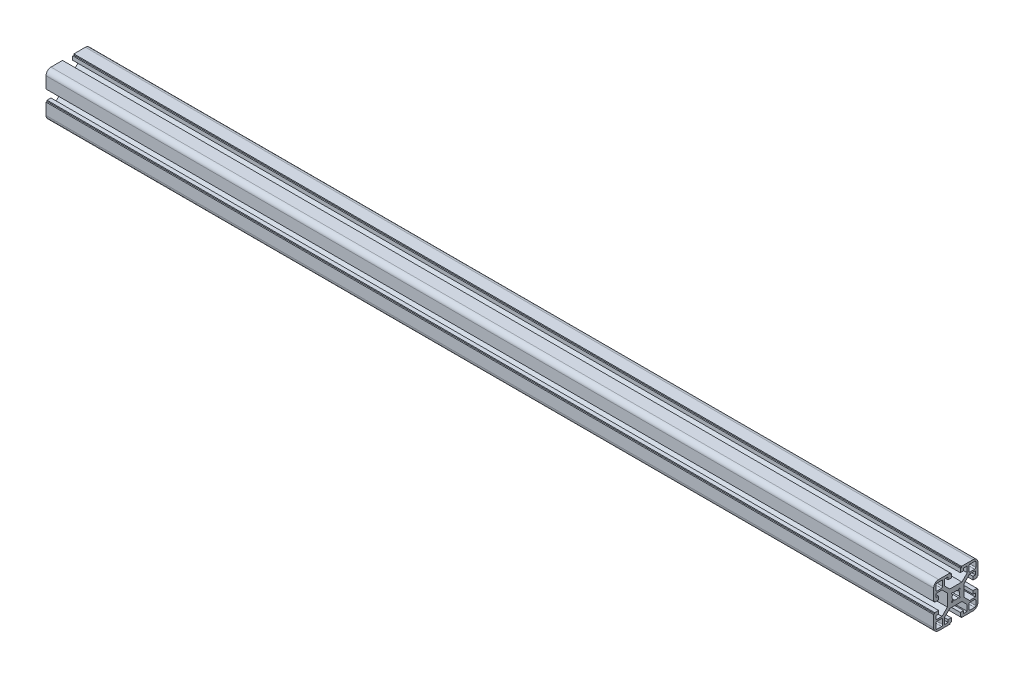
SolidWorks part; units mm, degrees
ref_plane "前视基准面" through (0, 0, 0) normal (0, 0, 1) x (1, 0, 0)
ref_plane "上视基准面" through (0, 0, 0) normal (0, 1, 0) x (1, 0, 0)
ref_plane "右视基准面" through (0, 0, 0) normal (1, 0, 0) x (0, 0, -1)
other "Configuration Table"
sketch "草图1" plane through (0, 0, 0) normal (1, 0, 0) x (0, 0, -1)
  line L0 (4.82, 19.28) -> (3.82, 19.28)
  line L1 (3.82, 19.28) -> (3.82, 15.78)
  line L2 (3.82, 15.78) -> (6.7364, 15.78)
  line L3 (6.7364, 15.78) -> (6.7364, 18.03)
  line L4 (6.7364, 18.03) -> (10.02, 18.03)
  line L5 (10.02, 18.03) -> (10.02, 12.7013)
  line L6 (10.02, 12.7013) -> (5.1987, 7.88)
  line L7 (5.1987, 7.88) -> (-5.7586, 7.88)
  line L8 (-5.7586, 7.88) -> (-10.58, 12.7013)
  line L9 (-10.58, 12.7013) -> (-10.58, 18.03)
  line L10 (-10.58, 18.03) -> (-7.2963, 18.03)
  line L11 (-7.2963, 18.03) -> (-7.2963, 15.78)
  line L12 (-7.2963, 15.78) -> (-4.38, 15.78)
  line L13 (-4.38, 15.78) -> (-4.38, 19.28)
  line L14 (-4.38, 19.28) -> (-5.38, 19.28)
  line L15 (-5.38, 19.28) -> (-5.38, 20.28)
  line L16 (-5.38, 20.28) -> (-15.78, 20.28)
  line L17 (-20.28, 15.78) -> (-20.28, 5.38)
  line L18 (-20.28, 5.38) -> (-19.28, 5.38)
  line L19 (-19.28, 5.38) -> (-19.28, 4.38)
  line L20 (-19.28, 4.38) -> (-15.78, 4.38)
  line L21 (-15.78, 4.38) -> (-15.78, 7.2963)
  line L22 (-15.78, 7.2963) -> (-18.03, 7.2963)
  line L23 (-18.03, 7.2963) -> (-18.03, 10.58)
  line L24 (-18.03, 10.58) -> (-12.7013, 10.58)
  line L25 (-12.7013, 10.58) -> (-7.88, 5.7586)
  line L26 (-7.88, 5.7586) -> (-7.88, -5.1987)
  line L27 (-7.88, -5.1987) -> (-12.7013, -10.02)
  line L28 (-12.7013, -10.02) -> (-18.03, -10.02)
  line L29 (-18.03, -10.02) -> (-18.03, -6.7364)
  line L30 (-18.03, -6.7364) -> (-15.78, -6.7364)
  line L31 (-15.78, -6.7364) -> (-15.78, -3.82)
  line L32 (-15.78, -3.82) -> (-19.28, -3.82)
  line L33 (-19.28, -3.82) -> (-19.28, -4.82)
  line L34 (-19.28, -4.82) -> (-20.28, -4.82)
  line L35 (-20.28, -4.82) -> (-20.28, -15.22)
  line L36 (-15.78, -19.72) -> (-5.38, -19.72)
  line L37 (-5.38, -19.72) -> (-5.38, -18.72)
  line L38 (-5.38, -18.72) -> (-4.38, -18.72)
  line L39 (-4.38, -18.72) -> (-4.38, -15.22)
  line L40 (-4.38, -15.22) -> (-7.2963, -15.22)
  line L41 (-7.2963, -15.22) -> (-7.2963, -17.47)
  line L42 (-7.2963, -17.47) -> (-10.58, -17.47)
  line L43 (-10.58, -17.47) -> (-10.58, -12.1414)
  line L44 (-10.58, -12.1414) -> (-5.7586, -7.32)
  line L45 (-5.7586, -7.32) -> (5.1987, -7.32)
  line L46 (5.1987, -7.32) -> (10.02, -12.1414)
  line L47 (10.02, -12.1414) -> (10.02, -17.47)
  line L48 (10.02, -17.47) -> (6.7364, -17.47)
  line L49 (6.7364, -17.47) -> (6.7364, -15.22)
  line L50 (6.7364, -15.22) -> (3.82, -15.22)
  line L51 (3.82, -15.22) -> (3.82, -18.72)
  line L52 (3.82, -18.72) -> (4.82, -18.72)
  line L53 (4.82, -18.72) -> (4.82, -19.72)
  line L54 (4.82, -19.72) -> (15.22, -19.72)
  line L55 (19.72, -15.22) -> (19.72, -4.82)
  line L56 (19.72, -4.82) -> (18.72, -4.82)
  line L57 (18.72, -4.82) -> (18.72, -3.82)
  line L58 (18.72, -3.82) -> (15.22, -3.82)
  line L59 (15.22, -3.82) -> (15.22, -6.7364)
  line L60 (15.22, -6.7364) -> (17.47, -6.7364)
  line L61 (17.47, -6.7364) -> (17.47, -10.02)
  line L62 (17.47, -10.02) -> (12.1414, -10.02)
  line L63 (12.1414, -10.02) -> (7.32, -5.1987)
  line L64 (7.32, -5.1987) -> (7.32, 5.7586)
  line L65 (7.32, 5.7586) -> (12.1414, 10.58)
  line L66 (12.1414, 10.58) -> (17.47, 10.58)
  line L67 (17.47, 10.58) -> (17.47, 7.2963)
  line L68 (17.47, 7.2963) -> (15.22, 7.2963)
  line L69 (15.22, 7.2963) -> (15.22, 4.38)
  line L70 (15.22, 4.38) -> (18.72, 4.38)
  line L71 (18.72, 4.38) -> (18.72, 5.38)
  line L72 (18.72, 5.38) -> (19.72, 5.38)
  line L73 (19.72, 5.38) -> (19.72, 15.78)
  line L74 (15.22, 20.28) -> (4.82, 20.28)
  line L75 (4.82, 20.28) -> (4.82, 19.28)
  line L76 (-13.08, -17.72) -> (-17.28, -17.72)
  line L77 (-18.28, -16.72) -> (-18.28, -12.52)
  line L78 (-17.28, -11.52) -> (-13.08, -11.52)
  line L79 (-12.08, -12.52) -> (-12.08, -16.72)
  line L80 (-17.28, 18.28) -> (-13.08, 18.28)
  line L81 (-12.08, 17.28) -> (-12.08, 13.08)
  line L82 (-13.08, 12.08) -> (-17.28, 12.08)
  line L83 (-18.28, 13.08) -> (-18.28, 17.28)
  line L84 (16.72, 12.08) -> (12.52, 12.08)
  line L85 (11.52, 13.08) -> (11.52, 17.28)
  line L86 (12.52, 18.28) -> (16.72, 18.28)
  line L87 (17.72, 17.28) -> (17.72, 13.08)
  line L88 (3.7505, -3.0434) -> (3.0434, -3.7505)
  line L89 (3.0434, -3.7505) -> (1.7445, -2.4516)
  line L90 (-2.3044, -2.4516) -> (-3.6033, -3.7505)
  line L91 (-3.6033, -3.7505) -> (-4.3104, -3.0434)
  line L92 (-4.3104, -3.0434) -> (-3.0115, -1.7445)
  line L93 (-3.0115, 2.3044) -> (-4.3104, 3.6033)
  line L94 (-4.3104, 3.6033) -> (-3.6033, 4.3104)
  line L95 (-3.6033, 4.3104) -> (-2.3044, 3.0115)
  line L96 (1.7445, 3.0115) -> (3.0434, 4.3104)
  line L97 (3.0434, 4.3104) -> (3.7505, 3.6033)
  line L98 (3.7505, 3.6033) -> (2.4516, 2.3044)
  line L99 (2.4516, -1.7445) -> (3.7505, -3.0434)
  line L100 (17.72, -12.52) -> (17.72, -16.72)
  line L101 (16.72, -17.72) -> (12.52, -17.72)
  line L102 (11.52, -16.72) -> (11.52, -12.52)
  line L103 (12.52, -11.52) -> (16.72, -11.52)
  arc A0 (-15.78, 20.28) -> (-20.28, 15.78) centre (-15.78, 15.78) ccw
  arc A1 (-20.28, -15.22) -> (-15.78, -19.72) centre (-15.78, -15.22) ccw
  arc A2 (15.22, -19.72) -> (19.72, -15.22) centre (15.22, -15.22) ccw
  arc A3 (19.72, 15.78) -> (15.22, 20.28) centre (15.22, 15.78) ccw
  arc A4 (-12.08, -16.72) -> (-13.08, -17.72) centre (-13.08, -16.72) cw
  arc A5 (-17.28, -17.72) -> (-18.28, -16.72) centre (-17.28, -16.72) cw
  arc A6 (-18.28, -12.52) -> (-17.28, -11.52) centre (-17.28, -12.52) cw
  arc A7 (-13.08, -11.52) -> (-12.08, -12.52) centre (-13.08, -12.52) cw
  arc A8 (-18.28, 17.28) -> (-17.28, 18.28) centre (-17.28, 17.28) cw
  arc A9 (-13.08, 18.28) -> (-12.08, 17.28) centre (-13.08, 17.28) cw
  arc A10 (-12.08, 13.08) -> (-13.08, 12.08) centre (-13.08, 13.08) cw
  arc A11 (-17.28, 12.08) -> (-18.28, 13.08) centre (-17.28, 13.08) cw
  arc A12 (17.72, 13.08) -> (16.72, 12.08) centre (16.72, 13.08) cw
  arc A13 (12.52, 12.08) -> (11.52, 13.08) centre (12.52, 13.08) cw
  arc A14 (11.52, 17.28) -> (12.52, 18.28) centre (12.52, 17.28) cw
  arc A15 (16.72, 18.28) -> (17.72, 17.28) centre (16.72, 17.28) cw
  arc A16 (1.7445, -2.4516) -> (-2.3044, -2.4516) centre (-0.28, 0.28) cw
  arc A17 (-3.0115, -1.7445) -> (-3.0115, 2.3044) centre (-0.28, 0.28) cw
  arc A18 (-2.3044, 3.0115) -> (1.7445, 3.0115) centre (-0.28, 0.28) cw
  arc A19 (2.4516, 2.3044) -> (2.4516, -1.7445) centre (-0.28, 0.28) cw
  arc A20 (16.72, -11.52) -> (17.72, -12.52) centre (16.72, -12.52) cw
  arc A21 (17.72, -16.72) -> (16.72, -17.72) centre (16.72, -16.72) cw
  arc A22 (12.52, -17.72) -> (11.52, -16.72) centre (12.52, -16.72) cw
  arc A23 (11.52, -12.52) -> (12.52, -11.52) centre (12.52, -12.52) cw
extrude "凸台-拉伸1" add sketch "草图1" against normal blind 50
sketch "草图2" plane through (0, 0, 0) normal (1, 0, 0) x (0, 0, -1)
  line L4 (-17.28, -17.72) -> (-13.08, -17.72)
  line L5 (-18.28, -12.52) -> (-18.28, -16.72)
  line L6 (-13.08, -11.52) -> (-17.28, -11.52)
  line L7 (-12.08, -16.72) -> (-12.08, -12.52)
  line L8 (-17.28, -17.72) -> (-13.08, -17.72)
  line L9 (-18.28, -12.52) -> (-18.28, -16.72)
  line L10 (-13.08, -11.52) -> (-17.28, -11.52)
  line L11 (-12.08, -16.72) -> (-12.08, -12.52)
  line L12 (-13.08, 18.28) -> (-17.28, 18.28)
  line L13 (-12.08, 13.08) -> (-12.08, 17.28)
  line L14 (-17.28, 12.08) -> (-13.08, 12.08)
  line L15 (-18.28, 17.28) -> (-18.28, 13.08)
  line L16 (-13.08, 18.28) -> (-17.28, 18.28)
  line L17 (-12.08, 13.08) -> (-12.08, 17.28)
  line L18 (-17.28, 12.08) -> (-13.08, 12.08)
  line L19 (-18.28, 17.28) -> (-18.28, 13.08)
  line L20 (11.52, 17.28) -> (11.52, 13.08)
  line L21 (16.72, 18.28) -> (12.52, 18.28)
  line L22 (17.72, 13.08) -> (17.72, 17.28)
  line L23 (12.52, 12.08) -> (16.72, 12.08)
  line L24 (11.52, 17.28) -> (11.52, 13.08)
  line L25 (16.72, 18.28) -> (12.52, 18.28)
  line L26 (17.72, 13.08) -> (17.72, 17.28)
  line L27 (12.52, 12.08) -> (16.72, 12.08)
  line L28 (11.52, -12.52) -> (11.52, -16.72)
  line L29 (16.72, -11.52) -> (12.52, -11.52)
  line L30 (17.72, -16.72) -> (17.72, -12.52)
  line L31 (12.52, -17.72) -> (16.72, -17.72)
  line L32 (11.52, -12.52) -> (11.52, -16.72)
  line L33 (16.72, -11.52) -> (12.52, -11.52)
  line L34 (17.72, -16.72) -> (17.72, -12.52)
  line L35 (12.52, -17.72) -> (16.72, -17.72)
  line L36 (-4.3104, 3.6033) -> (-3.0115, 2.3044)
  line L37 (-3.6033, 4.3104) -> (-4.3104, 3.6033)
  line L38 (-2.3044, 3.0115) -> (-3.6033, 4.3104)
  line L39 (3.0434, 4.3104) -> (1.7445, 3.0115)
  line L40 (3.7505, 3.6033) -> (3.0434, 4.3104)
  line L41 (2.4516, 2.3044) -> (3.7505, 3.6033)
  line L42 (3.7505, -3.0434) -> (2.4516, -1.7445)
  line L43 (3.0434, -3.7505) -> (3.7505, -3.0434)
  line L44 (1.7445, -2.4516) -> (3.0434, -3.7505)
  line L45 (-3.6033, -3.7505) -> (-2.3044, -2.4516)
  line L46 (-4.3104, -3.0434) -> (-3.6033, -3.7505)
  line L47 (-3.0115, -1.7445) -> (-4.3104, -3.0434)
  line L48 (-4.3104, 3.6033) -> (-3.0115, 2.3044)
  line L49 (-3.6033, 4.3104) -> (-4.3104, 3.6033)
  line L50 (-2.3044, 3.0115) -> (-3.6033, 4.3104)
  line L51 (3.0434, 4.3104) -> (1.7445, 3.0115)
  line L52 (3.7505, 3.6033) -> (3.0434, 4.3104)
  line L53 (2.4516, 2.3044) -> (3.7505, 3.6033)
  line L54 (3.7505, -3.0434) -> (2.4516, -1.7445)
  line L55 (3.0434, -3.7505) -> (3.7505, -3.0434)
  line L56 (1.7445, -2.4516) -> (3.0434, -3.7505)
  line L57 (-3.6033, -3.7505) -> (-2.3044, -2.4516)
  line L58 (-4.3104, -3.0434) -> (-3.6033, -3.7505)
  line L59 (-3.0115, -1.7445) -> (-4.3104, -3.0434)
  line L84 (19.72, 5.38) -> (19.72, 15.78)
  line L85 (18.72, 5.38) -> (19.72, 5.38)
  line L86 (18.72, 4.38) -> (18.72, 5.38)
  line L87 (15.22, 4.38) -> (18.72, 4.38)
  line L88 (15.22, 7.2963) -> (15.22, 4.38)
  line L89 (17.47, 7.2963) -> (15.22, 7.2963)
  line L90 (17.47, 10.58) -> (17.47, 7.2963)
  line L91 (12.1414, 10.58) -> (17.47, 10.58)
  line L92 (7.32, 5.7586) -> (12.1414, 10.58)
  line L93 (7.32, -5.1987) -> (7.32, 5.7586)
  line L94 (12.1414, -10.02) -> (7.32, -5.1987)
  line L95 (17.47, -10.02) -> (12.1414, -10.02)
  line L96 (17.47, -6.7364) -> (17.47, -10.02)
  line L97 (15.22, -6.7364) -> (17.47, -6.7364)
  line L98 (15.22, -3.82) -> (15.22, -6.7364)
  line L99 (18.72, -3.82) -> (15.22, -3.82)
  line L100 (18.72, -4.82) -> (18.72, -3.82)
  line L101 (19.72, -4.82) -> (18.72, -4.82)
  line L102 (19.72, -15.22) -> (19.72, -4.82)
  line L103 (4.82, -19.72) -> (15.22, -19.72)
  line L104 (4.82, -18.72) -> (4.82, -19.72)
  line L105 (3.82, -18.72) -> (4.82, -18.72)
  line L106 (3.82, -15.22) -> (3.82, -18.72)
  line L107 (6.7364, -15.22) -> (3.82, -15.22)
  line L108 (6.7364, -17.47) -> (6.7364, -15.22)
  line L109 (10.02, -17.47) -> (6.7364, -17.47)
  line L110 (10.02, -12.1414) -> (10.02, -17.47)
  line L111 (5.1987, -7.32) -> (10.02, -12.1414)
  line L112 (-5.7586, -7.32) -> (5.1987, -7.32)
  line L113 (-10.58, -12.1414) -> (-5.7586, -7.32)
  line L114 (-10.58, -17.47) -> (-10.58, -12.1414)
  line L115 (-7.2963, -17.47) -> (-10.58, -17.47)
  line L116 (-7.2963, -15.22) -> (-7.2963, -17.47)
  line L117 (-4.38, -15.22) -> (-7.2963, -15.22)
  line L118 (-4.38, -18.72) -> (-4.38, -15.22)
  line L119 (-5.38, -18.72) -> (-4.38, -18.72)
  line L120 (-5.38, -19.72) -> (-5.38, -18.72)
  line L121 (-15.78, -19.72) -> (-5.38, -19.72)
  line L122 (-20.28, -4.82) -> (-20.28, -15.22)
  line L123 (-19.28, -4.82) -> (-20.28, -4.82)
  line L124 (-19.28, -3.82) -> (-19.28, -4.82)
  line L125 (-15.78, -3.82) -> (-19.28, -3.82)
  line L126 (-15.78, -6.7364) -> (-15.78, -3.82)
  line L127 (-18.03, -6.7364) -> (-15.78, -6.7364)
  line L128 (-18.03, -10.02) -> (-18.03, -6.7364)
  line L129 (-12.7013, -10.02) -> (-18.03, -10.02)
  line L130 (-7.88, -5.1987) -> (-12.7013, -10.02)
  line L131 (-7.88, 5.7586) -> (-7.88, -5.1987)
  line L132 (-12.7013, 10.58) -> (-7.88, 5.7586)
  line L133 (-18.03, 10.58) -> (-12.7013, 10.58)
  line L134 (-18.03, 7.2963) -> (-18.03, 10.58)
  line L135 (-15.78, 7.2963) -> (-18.03, 7.2963)
  line L136 (-15.78, 4.38) -> (-15.78, 7.2963)
  line L137 (-19.28, 4.38) -> (-15.78, 4.38)
  line L138 (-19.28, 5.38) -> (-19.28, 4.38)
  line L139 (-20.28, 5.38) -> (-19.28, 5.38)
  line L140 (-20.28, 15.78) -> (-20.28, 5.38)
  line L141 (-5.38, 20.28) -> (-15.78, 20.28)
  line L142 (-5.38, 19.28) -> (-5.38, 20.28)
  line L143 (-4.38, 19.28) -> (-5.38, 19.28)
  line L144 (-4.38, 15.78) -> (-4.38, 19.28)
  line L145 (-7.2963, 15.78) -> (-4.38, 15.78)
  line L146 (-7.2963, 18.03) -> (-7.2963, 15.78)
  line L147 (-10.58, 18.03) -> (-7.2963, 18.03)
  line L148 (-10.58, 12.7013) -> (-10.58, 18.03)
  line L149 (-5.7586, 7.88) -> (-10.58, 12.7013)
  line L150 (5.1987, 7.88) -> (-5.7586, 7.88)
  line L151 (10.02, 12.7013) -> (5.1987, 7.88)
  line L152 (10.02, 18.03) -> (10.02, 12.7013)
  line L153 (6.7364, 18.03) -> (10.02, 18.03)
  line L154 (6.7364, 15.78) -> (6.7364, 18.03)
  line L155 (3.82, 15.78) -> (6.7364, 15.78)
  line L156 (3.82, 19.28) -> (3.82, 15.78)
  line L157 (4.82, 19.28) -> (3.82, 19.28)
  line L158 (4.82, 20.28) -> (4.82, 19.28)
  line L159 (15.22, 20.28) -> (4.82, 20.28)
  line L160 (19.72, 5.38) -> (19.72, 15.78)
  line L161 (18.72, 5.38) -> (19.72, 5.38)
  line L162 (18.72, 4.38) -> (18.72, 5.38)
  line L163 (15.22, 4.38) -> (18.72, 4.38)
  line L164 (15.22, 7.2963) -> (15.22, 4.38)
  line L165 (17.47, 7.2963) -> (15.22, 7.2963)
  line L166 (17.47, 10.58) -> (17.47, 7.2963)
  line L167 (12.1414, 10.58) -> (17.47, 10.58)
  line L168 (7.32, 5.7586) -> (12.1414, 10.58)
  line L169 (7.32, -5.1987) -> (7.32, 5.7586)
  line L170 (12.1414, -10.02) -> (7.32, -5.1987)
  line L171 (17.47, -10.02) -> (12.1414, -10.02)
  line L172 (17.47, -6.7364) -> (17.47, -10.02)
  line L173 (15.22, -6.7364) -> (17.47, -6.7364)
  line L174 (15.22, -3.82) -> (15.22, -6.7364)
  line L175 (18.72, -3.82) -> (15.22, -3.82)
  line L176 (18.72, -4.82) -> (18.72, -3.82)
  line L177 (19.72, -4.82) -> (18.72, -4.82)
  line L178 (19.72, -15.22) -> (19.72, -4.82)
  line L179 (4.82, -19.72) -> (15.22, -19.72)
  line L180 (4.82, -18.72) -> (4.82, -19.72)
  line L181 (3.82, -18.72) -> (4.82, -18.72)
  line L182 (3.82, -15.22) -> (3.82, -18.72)
  line L183 (6.7364, -15.22) -> (3.82, -15.22)
  line L184 (6.7364, -17.47) -> (6.7364, -15.22)
  line L185 (10.02, -17.47) -> (6.7364, -17.47)
  line L186 (10.02, -12.1414) -> (10.02, -17.47)
  line L187 (5.1987, -7.32) -> (10.02, -12.1414)
  line L188 (-5.7586, -7.32) -> (5.1987, -7.32)
  line L189 (-10.58, -12.1414) -> (-5.7586, -7.32)
  line L190 (-10.58, -17.47) -> (-10.58, -12.1414)
  line L191 (-7.2963, -17.47) -> (-10.58, -17.47)
  line L192 (-7.2963, -15.22) -> (-7.2963, -17.47)
  line L193 (-4.38, -15.22) -> (-7.2963, -15.22)
  line L194 (-4.38, -18.72) -> (-4.38, -15.22)
  line L195 (-5.38, -18.72) -> (-4.38, -18.72)
  line L196 (-5.38, -19.72) -> (-5.38, -18.72)
  line L197 (-15.78, -19.72) -> (-5.38, -19.72)
  line L198 (-20.28, -4.82) -> (-20.28, -15.22)
  line L199 (-19.28, -4.82) -> (-20.28, -4.82)
  line L200 (-19.28, -3.82) -> (-19.28, -4.82)
  line L201 (-15.78, -3.82) -> (-19.28, -3.82)
  line L202 (-15.78, -6.7364) -> (-15.78, -3.82)
  line L203 (-18.03, -6.7364) -> (-15.78, -6.7364)
  line L204 (-18.03, -10.02) -> (-18.03, -6.7364)
  line L205 (-12.7013, -10.02) -> (-18.03, -10.02)
  line L206 (-7.88, -5.1987) -> (-12.7013, -10.02)
  line L207 (-7.88, 5.7586) -> (-7.88, -5.1987)
  line L208 (-12.7013, 10.58) -> (-7.88, 5.7586)
  line L209 (-18.03, 10.58) -> (-12.7013, 10.58)
  line L210 (-18.03, 7.2963) -> (-18.03, 10.58)
  line L211 (-15.78, 7.2963) -> (-18.03, 7.2963)
  line L212 (-15.78, 4.38) -> (-15.78, 7.2963)
  line L213 (-19.28, 4.38) -> (-15.78, 4.38)
  line L214 (-19.28, 5.38) -> (-19.28, 4.38)
  line L215 (-20.28, 5.38) -> (-19.28, 5.38)
  line L216 (-20.28, 15.78) -> (-20.28, 5.38)
  line L217 (-5.38, 20.28) -> (-15.78, 20.28)
  line L218 (-5.38, 19.28) -> (-5.38, 20.28)
  line L219 (-4.38, 19.28) -> (-5.38, 19.28)
  line L220 (-4.38, 15.78) -> (-4.38, 19.28)
  line L221 (-7.2963, 15.78) -> (-4.38, 15.78)
  line L222 (-7.2963, 18.03) -> (-7.2963, 15.78)
  line L223 (-10.58, 18.03) -> (-7.2963, 18.03)
  line L224 (-10.58, 12.7013) -> (-10.58, 18.03)
  line L225 (-5.7586, 7.88) -> (-10.58, 12.7013)
  line L226 (5.1987, 7.88) -> (-5.7586, 7.88)
  line L227 (10.02, 12.7013) -> (5.1987, 7.88)
  line L228 (10.02, 18.03) -> (10.02, 12.7013)
  line L229 (6.7364, 18.03) -> (10.02, 18.03)
  line L230 (6.7364, 15.78) -> (6.7364, 18.03)
  line L231 (3.82, 15.78) -> (6.7364, 15.78)
  line L232 (3.82, 19.28) -> (3.82, 15.78)
  line L233 (4.82, 19.28) -> (3.82, 19.28)
  line L234 (4.82, 20.28) -> (4.82, 19.28)
  line L235 (15.22, 20.28) -> (4.82, 20.28)
  arc A4 (-18.28, -16.72) -> (-17.28, -17.72) centre (-17.28, -16.72) ccw
  arc A5 (-17.28, -11.52) -> (-18.28, -12.52) centre (-17.28, -12.52) ccw
  arc A6 (-12.08, -12.52) -> (-13.08, -11.52) centre (-13.08, -12.52) ccw
  arc A7 (-13.08, -17.72) -> (-12.08, -16.72) centre (-13.08, -16.72) ccw
  arc A8 (-18.28, -16.72) -> (-17.28, -17.72) centre (-17.28, -16.72) ccw
  arc A9 (-17.28, -11.52) -> (-18.28, -12.52) centre (-17.28, -12.52) ccw
  arc A10 (-12.08, -12.52) -> (-13.08, -11.52) centre (-13.08, -12.52) ccw
  arc A11 (-13.08, -17.72) -> (-12.08, -16.72) centre (-13.08, -16.72) ccw
  arc A12 (15.22, -19.72) -> (19.72, -15.22) centre (15.22, -15.22) ccw
  arc A13 (-20.28, -15.22) -> (-15.78, -19.72) centre (-15.78, -15.22) ccw
  arc A14 (-15.78, 20.28) -> (-20.28, 15.78) centre (-15.78, 15.78) ccw
  arc A15 (19.72, 15.78) -> (15.22, 20.28) centre (15.22, 15.78) ccw
  arc A16 (15.22, -19.72) -> (19.72, -15.22) centre (15.22, -15.22) ccw
  arc A17 (-20.28, -15.22) -> (-15.78, -19.72) centre (-15.78, -15.22) ccw
  arc A18 (-15.78, 20.28) -> (-20.28, 15.78) centre (-15.78, 15.78) ccw
  arc A19 (19.72, 15.78) -> (15.22, 20.28) centre (15.22, 15.78) ccw
  arc A20 (-12.08, 17.28) -> (-13.08, 18.28) centre (-13.08, 17.28) ccw
  arc A21 (-13.08, 12.08) -> (-12.08, 13.08) centre (-13.08, 13.08) ccw
  arc A22 (-18.28, 13.08) -> (-17.28, 12.08) centre (-17.28, 13.08) ccw
  arc A23 (-17.28, 18.28) -> (-18.28, 17.28) centre (-17.28, 17.28) ccw
  arc A24 (-12.08, 17.28) -> (-13.08, 18.28) centre (-13.08, 17.28) ccw
  arc A25 (-13.08, 12.08) -> (-12.08, 13.08) centre (-13.08, 13.08) ccw
  arc A26 (-18.28, 13.08) -> (-17.28, 12.08) centre (-17.28, 13.08) ccw
  arc A27 (-17.28, 18.28) -> (-18.28, 17.28) centre (-17.28, 17.28) ccw
  arc A28 (12.52, 18.28) -> (11.52, 17.28) centre (12.52, 17.28) ccw
  arc A29 (17.72, 17.28) -> (16.72, 18.28) centre (16.72, 17.28) ccw
  arc A30 (16.72, 12.08) -> (17.72, 13.08) centre (16.72, 13.08) ccw
  arc A31 (11.52, 13.08) -> (12.52, 12.08) centre (12.52, 13.08) ccw
  arc A32 (12.52, 18.28) -> (11.52, 17.28) centre (12.52, 17.28) ccw
  arc A33 (17.72, 17.28) -> (16.72, 18.28) centre (16.72, 17.28) ccw
  arc A34 (16.72, 12.08) -> (17.72, 13.08) centre (16.72, 13.08) ccw
  arc A35 (11.52, 13.08) -> (12.52, 12.08) centre (12.52, 13.08) ccw
  arc A36 (1.7445, 3.0115) -> (-2.3044, 3.0115) centre (-0.28, 0.28) ccw
  arc A37 (2.4516, -1.7445) -> (2.4516, 2.3044) centre (-0.28, 0.28) ccw
  arc A38 (-2.3044, -2.4516) -> (1.7445, -2.4516) centre (-0.28, 0.28) ccw
  arc A39 (-3.0115, 2.3044) -> (-3.0115, -1.7445) centre (-0.28, 0.28) ccw
  arc A40 (1.7445, 3.0115) -> (-2.3044, 3.0115) centre (-0.28, 0.28) ccw
  arc A41 (2.4516, -1.7445) -> (2.4516, 2.3044) centre (-0.28, 0.28) ccw
  arc A42 (-2.3044, -2.4516) -> (1.7445, -2.4516) centre (-0.28, 0.28) ccw
  arc A43 (-3.0115, 2.3044) -> (-3.0115, -1.7445) centre (-0.28, 0.28) ccw
  arc A44 (12.52, -11.52) -> (11.52, -12.52) centre (12.52, -12.52) ccw
  arc A45 (17.72, -12.52) -> (16.72, -11.52) centre (16.72, -12.52) ccw
  arc A46 (16.72, -17.72) -> (17.72, -16.72) centre (16.72, -16.72) ccw
  arc A47 (11.52, -16.72) -> (12.52, -17.72) centre (12.52, -16.72) ccw
  arc A48 (12.52, -11.52) -> (11.52, -12.52) centre (12.52, -12.52) ccw
  arc A49 (17.72, -12.52) -> (16.72, -11.52) centre (16.72, -12.52) ccw
  arc A50 (16.72, -17.72) -> (17.72, -16.72) centre (16.72, -16.72) ccw
  arc A51 (11.52, -16.72) -> (12.52, -17.72) centre (12.52, -16.72) ccw
  dimension "D1" = 0
  dimension "D2" = 0
  dimension "D3" = 0
  dimension "D4" = 0
  dimension "D5" = 0
  dimension "D6" = 0
extrude "凸台-拉伸2" add sketch "草图2" against normal blind 800
